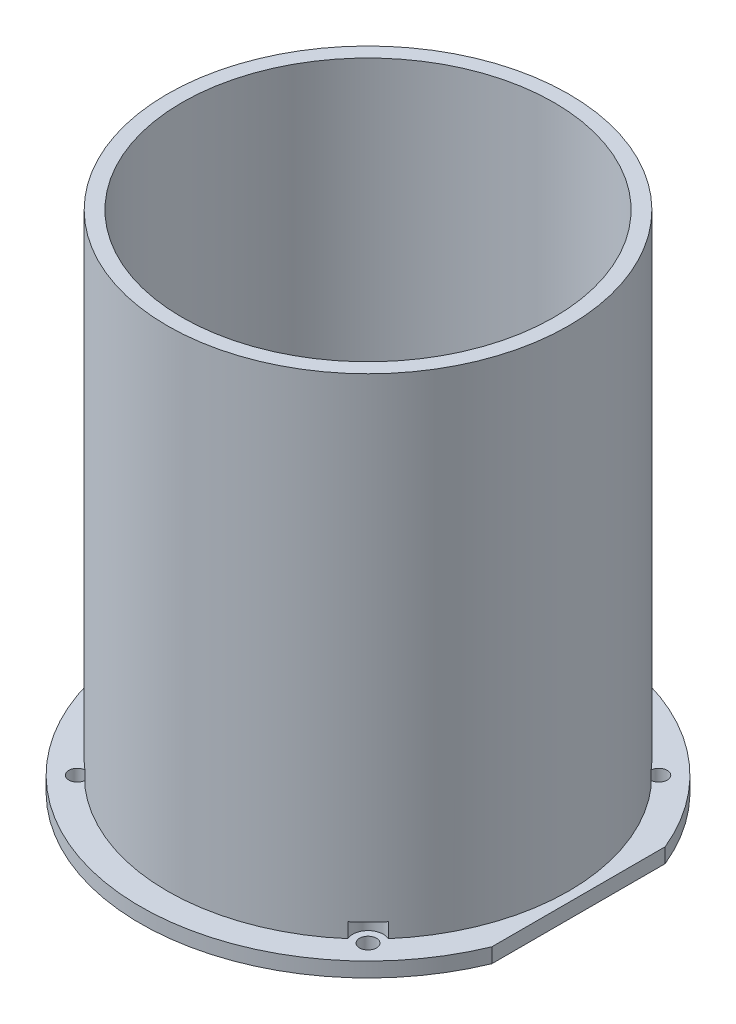
SolidWorks part; units mm, degrees
material "ABS"
ref_plane "Front" through (0, 0, 0) normal (0, 0, 1) x (1, 0, 0)
ref_plane "Top" through (0, 0, 0) normal (0, 1, 0) x (1, 0, 0)
ref_plane "Right" through (0, 0, 0) normal (1, 0, 0) x (0, 0, -1)
sketch "Sketch1" plane through (0, 0, 0) normal (0, 1, 0) x (1, 0, 0)
  circle A0 centre (0, 0) radius 46.5
  circle A1 centre (0, 0) radius 38
  dimension "D1" = 93
  dimension "D2" = 76
extrude "Boss-Extrude1" add sketch "Sketch1" along normal blind 3
sketch "Sketch2" plane through (0, 3, 0) normal (0, 1, 0) x (1, 0, 0)
  circle A0 centre (0, 0) radius 41
  circle A1 centre (0, 0) radius 38
  circle A2 centre (0, 0) radius 38 construction
  dimension "D1" = 3
extrude "Boss-Extrude2" add sketch "Sketch2" along normal blind 100
hole_wizard "#4 Clearance Hole1" positions "Sketch3" profile "Sketch4" hole size "#4" standard "ANSI Inch"
sketch "Sketch3" plane through (0, 3, 0) normal (0, 1, 0) x (1, 0, 0)
  line L0 (-29.6985, -29.6985) -> (29.6985, 29.6985) construction
  line L1 (29.6985, -29.6985) -> (-29.6985, 29.6985) construction
  point P0 (-29.6985, 29.6985)
  point P2 (29.6985, 29.6985)
  point P4 (29.6985, -29.6985)
  point P6 (-29.6985, -29.6985)
  point P14 (0, 0)
  point P16 (0, 0)
  dimension "D1" = 84
sketch "Sketch4" plane through (-29.6985, 3, -29.6985) normal (1, 0, 0) x (0, 0, 1)
  line L0 (0, 0) -> (0, 3)
  line L1 (0, 3) -> (1.7272, 3)
  line L2 (1.7272, 3) -> (1.7272, 0)
  line L5 (1.7272, 0) -> (0, 0)
  line L11 (0, -6.35) -> (0, 107.95) construction
  dimension "Thru Hole Dia." = 3.4544
  dimension "Thru Hole Depth" = 3
sketch "Sketch5" plane through (0, 3, 0) normal (0, 1, 0) x (1, 0, 0)
  circle A0 centre (-29.6985, 29.6985) radius 3.125
  dimension "D1" = 6.25
extrude "Cut-Extrude1" cut sketch "Sketch5" along normal blind 3
sketch "Sketch6" plane through (0, 3, 0) normal (0, 1, 0) x (1, 0, 0)
  arc A0 (-31.8903, 25.7684) -> (-25.7684, 31.8903) centre (-29.6985, 29.6985) ccw
  arc A1 (27.991, 29.9584) -> (-26.8505, 30.9847) centre (0, 0) ccw construction
  arc A2 (-30.9847, 26.8505) -> (-29.9584, -27.991) centre (0, 0) ccw construction
  arc A3 (-30.9847, 26.8505) -> (-26.8505, 30.9847) centre (-29.6985, 29.6985) ccw construction
  arc A4 (-25.7684, 31.8903) -> (-26.8505, 30.9847) centre (0, 0) ccw
  arc A5 (-30.9847, 26.8505) -> (-31.8903, 25.7684) centre (0, 0) ccw
  arc A6 (-30.9847, 26.8505) -> (-26.8505, 30.9847) centre (-29.6985, 29.6985) ccw
  dimension "D1" = 9
extrude "Boss-Extrude3" add sketch "Sketch6" along normal blind 5 and the other way blind 2
pattern_circular "CirPattern3" count 4 over 360 about axis through (0, 0, 0) along (0, 1, 0) of "Boss-Extrude3", "Cut-Extrude1"
sketch "Sketch7" plane through (0, 3, 0) normal (0, 1, 0) x (1, 0, 0)
  line L0 (43, -17.6989) -> (43, 17.6989)
  circle A0 centre (0, 0) radius 46.5 construction
  arc A1 (43, -17.6989) -> (43, 17.6989) centre (0, 0) ccw
  dimension "D1" = 43
extrude "Cut-Extrude2" cut sketch "Sketch7" against normal through all
